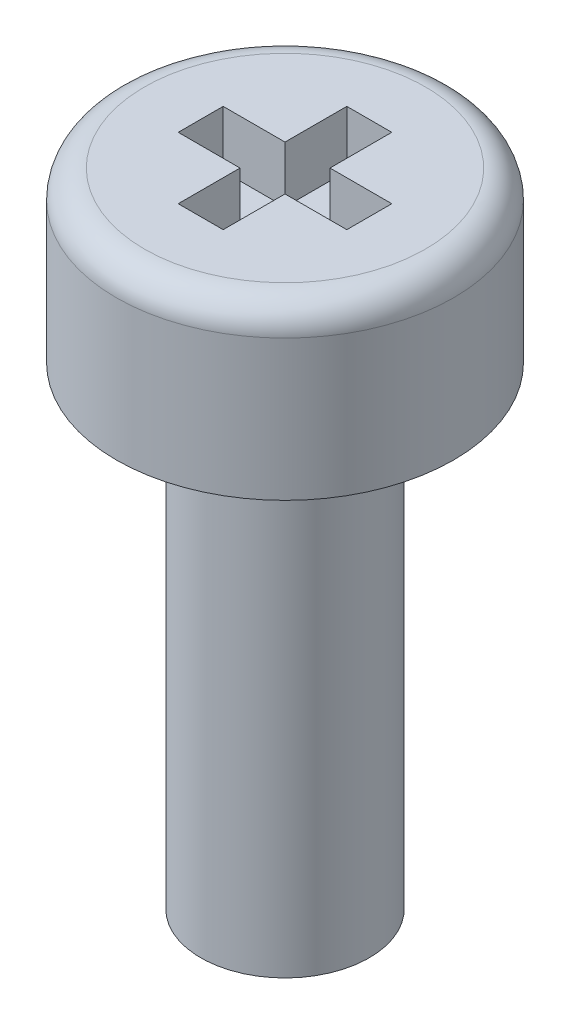
SolidWorks part; units mm, degrees
ref_plane "Front Plane" through (0, 0, 0) normal (0, 0, 1) x (1, 0, 0)
ref_plane "Top Plane" through (0, 0, 0) normal (0, 1, 0) x (1, 0, 0)
ref_plane "Right Plane" through (0, 0, 0) normal (1, 0, 0) x (0, 0, -1)
sketch "Sketch1" plane through (0, 0, 0) normal (0, 1, 0) x (1, 0, 0)
  circle A0 centre (0, 0) radius 3
  dimension "D1" = 6
extrude "Boss-Extrude1" add sketch "Sketch1" along normal blind 3
sketch "Sketch2" plane through (0, 0, 0) normal (0, -1, 0) x (1, 0, 0)
  circle A0 centre (0, 0) radius 1.5
  dimension "D1" = 3
extrude "Boss-Extrude2" add sketch "Sketch2" along normal blind 8.42
fillet "Fillet1" radius 0.5 1 edges at (0, 3, 3)
sketch "Sketch3" plane through (0, 3, 0) normal (0, 1, 0) x (1, 0, 0)
  line L1 (0.4, 1.5) -> (-0.4, 1.5)
  line L2 (0.4, 1.5) -> (0.4, -1.5)
  line L3 (0.4, -1.5) -> (-0.4, -1.5)
  line L4 (-0.4, 1.5) -> (-0.4, -1.5)
  line L5 (0.4, 1.5) -> (-0.4, -1.5) construction
  line L6 (0.4, -1.5) -> (-0.4, 1.5) construction
  line L7 (-1.5, 0.4) -> (1.5, 0.4)
  line L8 (-1.5, 0.4) -> (-1.5, -0.4)
  line L9 (-1.5, -0.4) -> (1.5, -0.4)
  line L10 (1.5, 0.4) -> (1.5, -0.4)
  line L11 (-1.5, 0.4) -> (1.5, -0.4) construction
  line L12 (-1.5, -0.4) -> (1.5, 0.4) construction
  point P0 (0, 0)
  point P6 (0, 0)
  dimension "D1" = 0.8
  dimension "D2" = 0.8
  dimension "D3" = 3
  dimension "D4" = 3
extrude "Cut-Extrude1" cut sketch "Sketch3" against normal blind 1 contours L4 L7 L2 L1 | L10 L7 L2 L9 | L9 L4 L3 L2 | L8 L9 L4 L7 | L4 L9 L2 L7
